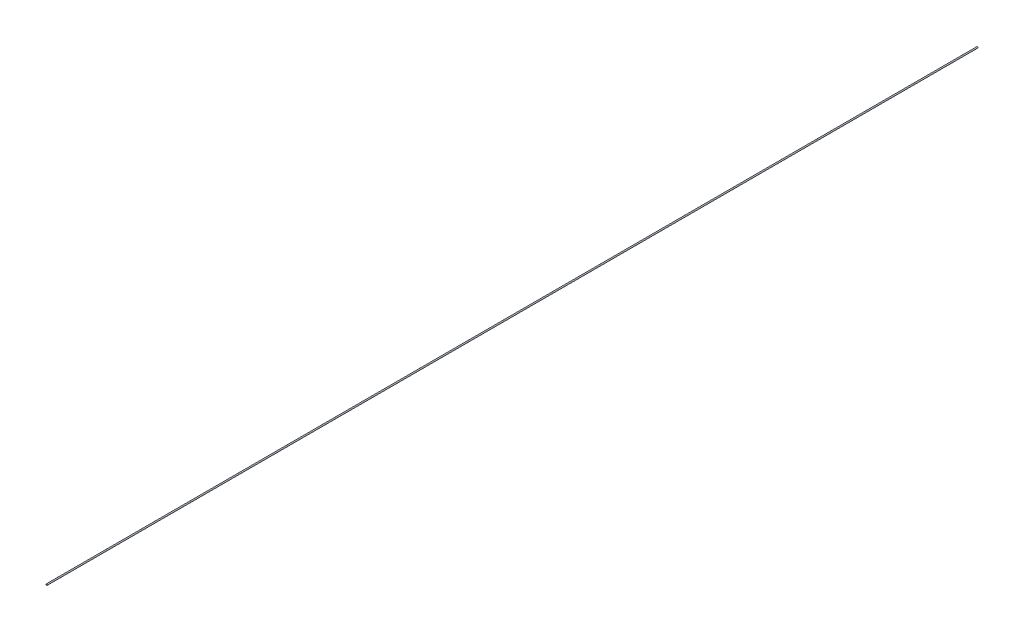
SolidWorks part; units mm, degrees
material "AISI 1020"
ref_plane "Спереди" through (0, 0, 0) normal (0, 0, 1) x (1, 0, 0)
ref_plane "Сверху" through (0, 0, 0) normal (0, 1, 0) x (1, 0, 0)
ref_plane "Справа" through (0, 0, 0) normal (1, 0, 0) x (0, 0, -1)
sketch "Эскиз1" plane through (0, 0, 0) normal (0, 0, 1) x (1, 0, 0)
  circle A0 centre (0, 0) radius 6
  dimension "D1" = 12
extrude "Бобышка-Вытянуть1" add sketch "Эскиз1" against normal blind 9000
